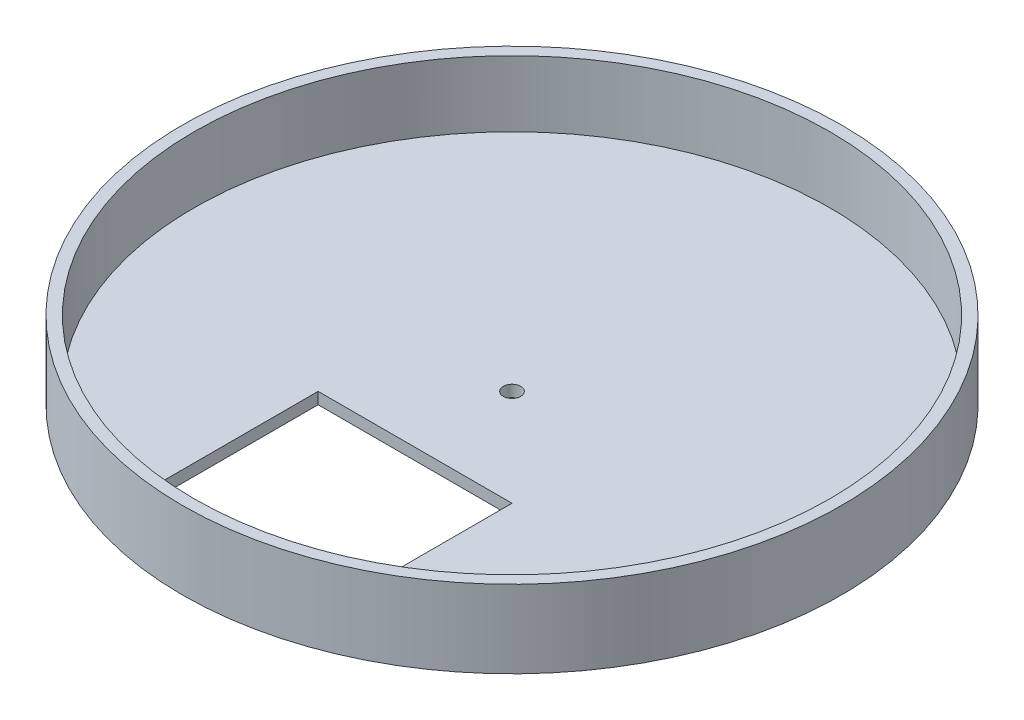
SolidWorks part; units mm, degrees
material "AISI 1020"
ref_plane "Front Plane" through (0, 0, 0) normal (0, 0, 1) x (1, 0, 0)
ref_plane "Top Plane" through (0, 0, 0) normal (0, 1, 0) x (1, 0, 0)
ref_plane "Right Plane" through (0, 0, 0) normal (1, 0, 0) x (0, 0, -1)
sketch "Sketch1" plane through (0, 0, 0) normal (0, 1, 0) x (1, 0, 0)
  circle A0 centre (0, 0) radius 215.9
  dimension "D1" = 431.8
extrude "Boss-Extrude1" add sketch "Sketch1" along normal blind 50.8
sketch "Sketch2" plane through (0, 50.8, 0) normal (0, 1, 0) x (1, 0, 0)
  circle A0 centre (0, 0) radius 208.28
  dimension "D1" = 416.56
extrude "Cut-Extrude1" cut sketch "Sketch2" against normal blind 43.18 contours A0
sketch "Sketch3" plane through (0, 7.62, 0) normal (0, 1, 0) x (1, 0, 0)
  line L0 (-63.5, -63.5) -> (63.5, -63.5)
  line L1 (63.5, -63.5) -> (63.5, -198.3641)
  line L2 (-63.5, -63.5) -> (-63.5, -198.3641)
  circle A0 centre (0, 0) radius 208.28 construction
  circle A1 centre (0, 0) radius 208.28 construction
  arc A2 (-63.5, -198.3641) -> (63.5, -198.3641) centre (0, 0) ccw
  point P2 (0, -63.5)
  dimension "D3" = 208.28
  dimension "D1" = 127
  dimension "D2" = 63.5
extrude "Cut-Extrude2" cut sketch "Sketch3" against normal through all
sketch "Sketch4" plane through (0, 7.62, 0) normal (0, 1, 0) x (1, 0, 0)
  circle A0 centre (0, 0) radius 5.715
  dimension "D1" = 11.43
extrude "Cut-Extrude3" cut sketch "Sketch4" against normal through all
